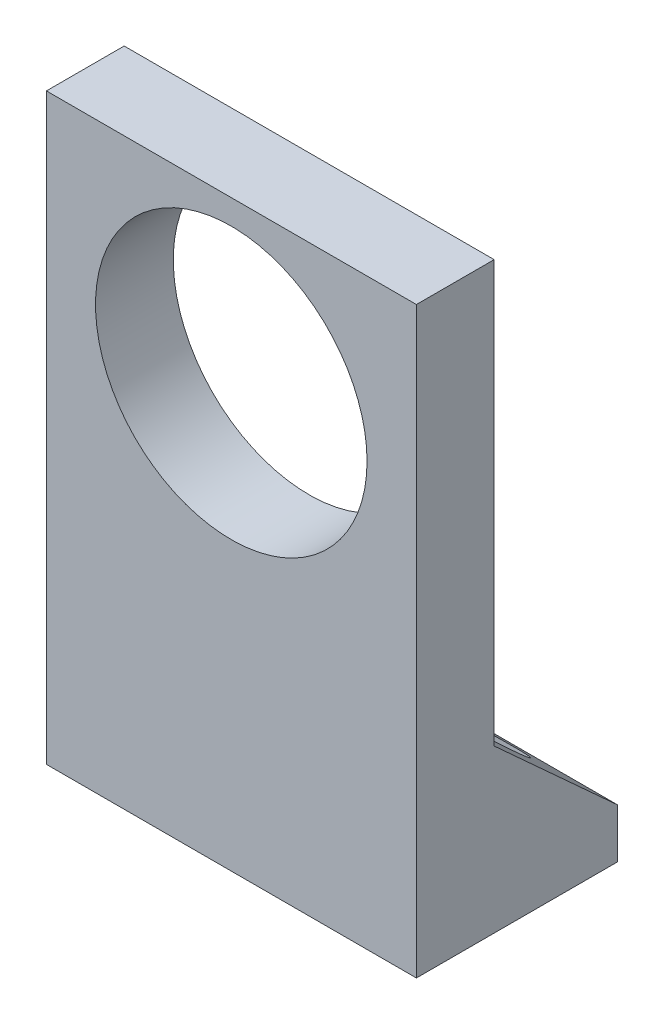
SolidWorks part; units mm, degrees
material "ABS"
ref_plane "Front Plane" through (0, 0, 0) normal (0, 0, 1) x (1, 0, 0)
ref_plane "Top Plane" through (0, 0, 0) normal (0, 1, 0) x (1, 0, 0)
ref_plane "Right Plane" through (0, 0, 0) normal (1, 0, 0) x (0, 0, -1)
sketch "Sketch1" plane through (0, 0, 0) normal (0, 0, 1) x (1, 0, 0)
  line L1 (-76.1871, 64.9281) -> (16.8129, 64.9281)
  line L2 (-76.1871, 64.9281) -> (-76.1871, -35.0719)
  line L3 (-76.1871, -35.0719) -> (16.8129, -35.0719)
  line L4 (16.8129, 64.9281) -> (16.8129, -35.0719)
  dimension "D1" = 93
  dimension "D2" = 100
extrude "Boss-Extrude2" add sketch "Sketch1" along normal blind 10 contours L1 L4 L3 L2
sketch "Sketch3" plane through (0, 0, 0) normal (0, 0, -1) x (-1, 0, 0)
  line L0 (76.1871, -35.0719) -> (-16.8129, -35.0719) construction
  line L1 (-16.8129, 64.9281) -> (-6.8129, 64.9281)
  line L2 (-16.8129, 64.9281) -> (-16.8129, -35.0719)
  line L3 (-16.8129, -35.0719) -> (-6.8129, -35.0719)
  line L4 (-6.8129, 64.9281) -> (-6.8129, -35.0719)
  line L5 (-16.8129, 64.9281) -> (-16.8129, -35.0719) construction
  dimension "D1" = 0
  dimension "D2" = 0
  dimension "D3" = 10
  dimension "D4" = 100
sketch "Sketch4" plane through (16.8129, 0, 0) normal (1, 0, 0) x (0, 0, -1)
  line L0 (-10, 64.9281) -> (-10, -35.0719) construction
  line L1 (-10, -5.0719) -> (0.01, -5.0719)
  line L2 (-10, -5.0719) -> (-10, -20.0719)
  line L3 (-10, -20.0719) -> (0.01, -20.0719)
  line L4 (0.01, -5.0719) -> (0.01, -20.0719)
  line L6 (-10, -35.0719) -> (0, -35.0719) construction
  dimension "D1" = 15
  dimension "D2" = 15
extrude "Boss-Extrude4" add sketch "Sketch4" along normal blind 24
sketch "Sketch5" plane through (0, -5.0719, 0) normal (0, 1, 0) x (1, 0, 0)
  line L0 (40.8129, -10) -> (16.8129, -10) construction
  line L2 (16.8129, 0) -> (16.8129, -10) construction
  circle A0 centre (26.8129, -5) radius 2
  dimension "D2" = 4
  dimension "D3" = 10
  dimension "D1" = 5
extrude "Cut-Extrude1" cut sketch "Sketch5" against normal blind 50
sketch "Sketch6" plane through (0, 0, 10) normal (0, 0, -1) x (-1, 0, 0)
  line L2 (76.1871, -35.0719) -> (-16.8129, -35.0719) construction
  line L3 (-16.8129, 64.9281) -> (-16.8129, -35.0719) construction
  circle A0 centre (-1.8129, -24.5719) radius 7.5
  dimension "D1" = 15
  dimension "D2" = 10.5
  dimension "D3" = 15
sketch "Sketch7" plane through (0, 0, 0) normal (0, 0, -1) x (-1, 0, 0)
  circle A0 centre (24.1871, 36.9281) radius 11
  circle A1 centre (24.1871, 36.9281) radius 9.3 construction
  dimension "D1" = 22
extrude "Cut-Extrude3" cut sketch "Sketch7" against normal blind 50
sketch "Sketch14" plane through (0, 0, 10) normal (0, 0, 1) x (1, 0, 0)
  line L0 (16.8129, 64.9281) -> (16.8129, -5.0719) construction
  line L1 (-44.6871, 15.7891) -> (16.8129, 15.7891)
  line L2 (-44.6871, 15.7891) -> (-44.6871, 57.7891)
  line L3 (-44.6871, 57.7891) -> (16.8129, 57.7891)
  line L4 (16.8129, 15.7891) -> (16.8129, 57.7891)
  dimension "D1" = 42
  dimension "D3" = 61.5
extrude "Cut-Extrude8" cut sketch "Sketch14" against normal blind 4
sketch "Sketch15" plane through (0, 0, 0) normal (0, 0, -1) x (-1, 0, 0)
  circle A0 centre (24.1871, 36.9281) radius 10
  circle A1 centre (24.1871, 36.9281) radius 11 construction
  dimension "D1" = 20
  dimension "D2" = 0
sketch "Sketch16" plane through (0, 0, 10) normal (0, 0, 1) x (1, 0, 0)
  line L0 (-43.6871, 56.9281) -> (14.3129, 56.9281) construction
  line L1 (-44.1871, 57.3281) -> (16.8129, 57.3281)
  line L2 (-44.1871, 57.3281) -> (-44.1871, 64.9281)
  line L3 (-44.1871, 64.9281) -> (16.8129, 64.9281)
  line L4 (16.8129, 57.3281) -> (16.8129, 64.9281)
  dimension "D1" = 0.4
sketch "Sketch17" plane through (0, 0, 10) normal (0, 0, 1) x (1, 0, 0)
  line L0 (16.8129, 15.7891) -> (16.8129, -5.0719) construction
  line L1 (-44.1871, 16.7281) -> (16.8129, 16.7281)
  line L2 (-44.1871, 16.7281) -> (-44.1871, -20.0719)
  line L3 (-44.1871, -20.0719) -> (16.8129, -20.0719)
  line L4 (16.8129, 16.7281) -> (16.8129, -20.0719)
  line L5 (-43.6871, 16.9281) -> (14.3129, 16.9281) construction
  line L6 (40.8129, -20.0719) -> (16.8129, -20.0719) construction
  line L9 (16.8129, -20.0719) -> (40.8129, -20.0719)
  line L10 (16.8129, -20.0719) -> (16.8129, -5.0719)
  line L11 (16.8129, -5.0719) -> (40.8129, -5.0719)
  line L12 (40.8129, -20.0719) -> (40.8129, -5.0719)
  line L13 (16.8129, -20.0719) -> (40.8129, -5.0719) construction
  line L14 (16.8129, -5.0719) -> (40.8129, -20.0719) construction
  point P16 (28.8129, -12.5719)
  dimension "D1" = 0.2
  dimension "D2" = 0
sketch "Sketch19" plane through (0, 0, 0) normal (0, 0, -1) x (-1, 0, 0)
  line L1 (-16.8129, 64.9281) -> (-16.8129, -35.0719) construction
  circle A0 centre (53.1871, 36.9281) radius 11
  circle A1 centre (24.1871, 36.9281) radius 10 construction
  dimension "D1" = 22
  dimension "D3" = 0
  dimension "D2" = 70
extrude "Cut-Extrude11" cut sketch "Sketch19" against normal blind 15
sketch "Sketch20" plane through (0, 0, 6) normal (0, 0, 1) x (1, 0, 0)
  circle A0 centre (-34.6871, 50.9281) radius 2
  circle A1 centre (5.3129, 50.9281) radius 2
  circle A2 centre (-34.6871, 22.9281) radius 2
  circle A3 centre (5.3129, 22.9281) radius 2
  arc A5 (-27.0471, 34.1316) -> (-27.0471, 39.7246) centre (-24.1871, 36.9281) ccw construction
  circle A6 centre (-24.1871, 36.9281) radius 11 construction
  dimension "D1" = 4
  dimension "D2" = 4
  dimension "D3" = 4
  dimension "D4" = 4
  dimension "D5" = 0
  dimension "D6" = 28
  dimension "D7" = 0
  dimension "D8" = 40
  dimension "D9" = 14
  dimension "D10" = 10.5
  dimension "D11" = 28
  dimension "D12" = 40
extrude "Cut-Extrude12" cut sketch "Sketch20" against normal blind 10
sketch "Sketch8" plane through (0, 64.9281, 0) normal (0, 1, 0) x (1, 0, 0)
  line L0 (-76.1871, -10) -> (16.8129, -10) construction
  line L5 (16.8129, 0) -> (12.3014, -10) construction
  line L6 (16.8129, -10) -> (7.8859, 0) construction
  line L8 (16.8129, -10) -> (16.8129, 0) construction
  line L9 (-76.1871, 0) -> (16.8129, 0) construction
  circle A0 centre (11.8129, -7) radius 1.4
  circle A1 centre (-13.1871, -7) radius 1.4
  point P4 (13.816, -6.6429)
  dimension "D1" = 25
  dimension "D2" = 5
  dimension "D3" = 2.8
  dimension "D4" = 7
  dimension "D5" = 7
sketch "Sketch21" plane through (0, 0, 0) normal (0, 0, -1) x (-1, 0, 0)
  line L1 (76.1871, 64.9281) -> (36.1871, 64.9281)
  line L2 (76.1871, 64.9281) -> (76.1871, 58.9281)
  line L3 (76.1871, 58.9281) -> (36.1871, 58.9281)
  line L4 (36.1871, 64.9281) -> (36.1871, 58.9281)
  dimension "D1" = 6
  dimension "D2" = 40
extrude "Boss-Extrude5" add sketch "Sketch21" along normal blind 27
sketch "Sketch22" plane through (0, 58.9281, 0) normal (0, -1, 0) x (1, 0, 0)
  line L0 (-76.1871, -27) -> (-76.1871, 0) construction
  line L1 (-36.1871, -27) -> (-76.1871, -27)
  line L2 (-36.1871, -27) -> (-36.1871, -20.7)
  line L3 (-36.1871, -20.7) -> (-76.1871, -20.7)
  line L4 (-76.1871, -27) -> (-76.1871, -20.7)
  dimension "D1" = 6.3
extrude "Boss-Extrude7" add sketch "Sketch22" along normal blind 40
sketch "Sketch23" plane through (0, 0, 10) normal (0, 0, 1) x (1, 0, 0)
  circle A0 centre (-53.1871, 36.9281) radius 8
  arc A1 (-44.6871, 43.9102) -> (-44.6871, 29.9459) centre (-53.1871, 36.9281) ccw construction
  dimension "D1" = 16
  dimension "D2" = 0
extrude "Cut-Extrude13" cut sketch "Sketch23" against normal blind 40
sketch "Sketch24" plane through (0, 0, 10) normal (0, 0, 1) x (1, 0, 0)
  line L1 (-76.1871, -35.0719) -> (42.0908, -35.0719)
  line L2 (-76.1871, -35.0719) -> (-76.1871, 6.7281)
  line L3 (-76.1871, 6.7281) -> (42.0908, 6.7281)
  line L4 (42.0908, -35.0719) -> (42.0908, 6.7281)
  dimension "D1" = 41.8
extrude "Cut-Extrude14" cut sketch "Sketch24" against normal blind 40
sketch "Sketch25" plane through (0, 0, 10) normal (0, 0, 1) x (1, 0, 0)
  line L5 (-44.6871, 29.9459) -> (-44.6871, 15.7891) construction
  line L6 (-76.1871, 6.7281) -> (-44.6871, 6.7281)
  line L7 (-76.1871, 6.7281) -> (-76.1871, 29.9281)
  line L8 (-76.1871, 29.9281) -> (-44.6871, 29.9281)
  line L9 (-44.6871, 6.7281) -> (-44.6871, 29.9281)
  arc A2 (-44.6871, 43.9102) -> (-44.6871, 29.9459) centre (-53.1871, 36.9281) ccw construction
  dimension "D1" = 7
extrude "Cut-Extrude15" cut sketch "Sketch25" against normal blind 20
sketch "Sketch26" plane through (0, 0, 6) normal (0, 0, 1) x (1, 0, 0)
  line L1 (-44.6871, 15.7891) -> (-36.2375, 15.7891)
  line L2 (-44.6871, 15.7891) -> (-44.6871, 21.6647)
  line L3 (-44.6871, 21.6647) -> (-36.2375, 21.6647)
  line L4 (-36.2375, 15.7891) -> (-36.2375, 21.6647)
  line L5 (-44.6871, 57.7891) -> (-36.2375, 57.7891)
  line L6 (-44.6871, 57.7891) -> (-44.6871, 52.1914)
  line L7 (-44.6871, 52.1914) -> (-36.2375, 52.1914)
  line L8 (-36.2375, 57.7891) -> (-36.2375, 52.1914)
  line L9 (6.8634, 52.1914) -> (14.3021, 52.1914)
  line L10 (6.8634, 52.1914) -> (6.8634, 57.7891)
  line L11 (6.8634, 57.7891) -> (14.3021, 57.7891)
  line L12 (14.3021, 52.1914) -> (14.3021, 57.7891)
  line L13 (6.8634, 20.9281) -> (14.3021, 20.9281)
  line L14 (6.8634, 20.9281) -> (6.8634, 15.7891)
  line L15 (6.8634, 15.7891) -> (14.3021, 15.7891)
  line L16 (14.3021, 20.9281) -> (14.3021, 15.7891)
  circle A0 centre (-34.6871, 22.9281) radius 2 construction
  circle A1 centre (-34.6871, 50.9281) radius 2 construction
  circle A2 centre (5.3129, 50.9281) radius 2 construction
  circle A3 centre (5.3129, 22.9281) radius 4
  circle A4 centre (5.3129, 50.9281) radius 4
  circle A5 centre (-34.6871, 50.9281) radius 4
  circle A6 centre (-34.6871, 22.9281) radius 4
  circle A7 centre (5.3129, 50.9281) radius 4
  circle A8 centre (5.3129, 22.9281) radius 4
  circle A9 centre (-34.6871, 50.9281) radius 4
  circle A10 centre (-34.6871, 22.9281) radius 4
  line M5 (-44.6871, 57.7891) -> (-44.6871, 43.9102)
  line M8 (-44.6871, 29.9281) -> (-44.6871, 15.7891)
  line M9 (-44.6871, 15.7891) -> (16.8129, 15.7891)
  line M11 (16.8129, 57.7891) -> (-44.6871, 57.7891)
  dimension "D1" = 8
  dimension "D2" = 8
  dimension "D3" = 8
  dimension "D4" = 8
extrude "Cut-Extrude18" cut sketch "Sketch26" against normal blind 3 contours A4 L9 L12 L10 M11 | A3 L14 L16 L13 M9 | A5 L8 L7 M11 M5 | A6 L3 L4 M8 M9
sketch "Sketch27" plane through (0, 0, 6) normal (0, 0, 1) x (1, 0, 0)
  circle A0 centre (5.3129, 50.9281) radius 4.1
  circle A1 centre (5.3129, 22.9281) radius 4
  circle A2 centre (-34.6871, 50.9281) radius 4.1
  circle A3 centre (-34.6871, 22.9281) radius 4.1
  dimension "D1" = 8.2
  dimension "D2" = 8.2
  dimension "D3" = 8
  dimension "D4" = 8.2
extrude "Cut-Extrude29" cut sketch "Sketch27" against normal blind 3
sketch "Sketch28" plane through (0, 0, 0) normal (0, 0, -1) x (-1, 0, 0)
  line L5 (-16.8129, 6.7281) -> (44.6871, 6.7281) construction
  line L6 (-16.8129, 64.9281) -> (12.6871, 64.9281)
  line L7 (-16.8129, 64.9281) -> (-16.8129, 6.7281)
  line L8 (-16.8129, 6.7281) -> (12.6871, 6.7281)
  line L9 (12.6871, 64.9281) -> (12.6871, 6.7281)
  circle A1 centre (34.6871, 22.9281) radius 2 construction
  dimension "D1" = 22
extrude "Cut-Extrude30" cut sketch "Sketch28" against normal blind 23
sketch "Sketch29" plane through (0, 15.7891, 0) normal (0, 1, 0) x (1, 0, 0)
  line L1 (-44.6871, -10) -> (-12.6871, -10)
  line L2 (-44.6871, -10) -> (-44.6871, -6)
  line L3 (-44.6871, -6) -> (-12.6871, -6)
  line L4 (-12.6871, -10) -> (-12.6871, -6)
extrude "Cut-Extrude31" cut sketch "Sketch29" against normal blind 23
sketch "Sketch31" plane through (0, 6.7281, 0) normal (0, -1, 0) x (1, 0, 0)
  line L1 (-44.6871, 6) -> (-12.6871, 6)
  line L2 (-44.6871, 6) -> (-44.6871, 0)
  line L3 (-44.6871, 0) -> (-12.6871, 0)
  line L4 (-12.6871, 6) -> (-12.6871, 0)
extrude "Boss-Extrude9" add sketch "Sketch31" along normal blind 6.6
sketch "Sketch32" plane through (0, 0, 6) normal (0, 0, 1) x (1, 0, 0)
  line L0 (-12.6871, 0.1281) -> (-12.6871, 57.7891) construction
  line L1 (-44.6871, 0.1281) -> (-12.6871, 0.1281)
  line L2 (-44.6871, 0.1281) -> (-44.6871, 6.1281)
  line L3 (-44.6871, 6.1281) -> (-12.6871, 6.1281)
  line L4 (-12.6871, 0.1281) -> (-12.6871, 6.1281)
  dimension "D1" = 6
extrude "Boss-Extrude10" add sketch "Sketch32" along normal blind 10
sketch "Sketch33" plane through (0, 6.1281, 0) normal (0, 1, 0) x (1, 0, 0)
  line L0 (-12.6871, -16) -> (-44.6871, -16) construction
  line L1 (-44.6871, -16) -> (-44.6871, -6) construction
  line L2 (-12.6871, -16) -> (-12.6871, -6) construction
  circle A0 centre (-37.6871, -11) radius 2
  circle A1 centre (-19.6871, -11) radius 2
  point P8 (-44.6871, -11)
  dimension "D1" = 4
  dimension "D2" = 4
  dimension "D3" = 0
  dimension "D4" = 5
  dimension "D5" = 7
  dimension "D6" = 7
extrude "Cut-Extrude32" cut sketch "Sketch33" against normal blind 10
sketch "Sketch34" plane through (-12.6871, 0, 0) normal (1, 0, 0) x (0, 0, -1)
  line L0 (-16, 6.1281) -> (-6, 6.1281)
  line L1 (-6, 6.1281) -> (-6, 14.0584)
  line L2 (-6, 6.1281) -> (-6, 57.7891) construction
  line L3 (-6, 14.0584) -> (-16, 6.1281)
extrude "Boss-Extrude11" add sketch "Sketch34" against normal up to vertex
sketch "Sketch35" plane through (0, 6.1281, 0) normal (0, -1, 0) x (1, 0, 0)
  circle A0 centre (-19.6871, 11) radius 3.5
  circle A1 centre (-37.6871, 11) radius 3.5
  dimension "D1" = 7
  dimension "D2" = 7
extrude "Cut-Extrude33" cut sketch "Sketch35" against normal blind 10
sketch "Sketch36" plane through (0, 18.9281, 0) normal (0, -1, 0) x (1, 0, 0)
  line L1 (-76.1871, -20.7) -> (-36.1871, -20.7)
  line L2 (-76.1871, -20.7) -> (-76.1871, -27)
  line L3 (-76.1871, -27) -> (-36.1871, -27)
  line L4 (-36.1871, -20.7) -> (-36.1871, -27)
extrude "Boss-Extrude12" add sketch "Sketch36" along normal up to vertex (18.8 mm away)
sketch "Sketch37" plane through (0, 0, -20.7) normal (0, 0, 1) x (1, 0, 0)
  line L0 (-76.1871, 0.1281) -> (-76.1871, 58.9281) construction
  line L1 (-36.1871, 0.1281) -> (-76.1871, 0.1281)
  line L2 (-36.1871, 0.1281) -> (-36.1871, 6.1281)
  line L3 (-36.1871, 6.1281) -> (-76.1871, 6.1281)
  line L4 (-76.1871, 0.1281) -> (-76.1871, 6.1281)
  dimension "D1" = 6
extrude "Boss-Extrude13" add sketch "Sketch37" along normal blind 16
sketch "Sketch38" plane through (0, 6.1281, 0) normal (0, 1, 0) x (1, 0, 0)
  line L0 (-36.1871, 4.7) -> (-76.1871, 4.7) construction
  line L2 (-36.1871, 4.7) -> (-36.1871, 20.7) construction
  circle A0 centre (-58.1871, 10.7) radius 2
  circle A1 centre (-45.1871, 10.7) radius 2
  dimension "D1" = 4
  dimension "D2" = 4
  dimension "D3" = 6
  dimension "D4" = 13
  dimension "D5" = 9
  dimension "D6" = 6
extrude "Cut-Extrude34" cut sketch "Sketch38" against normal blind 16
sketch "Sketch39" plane through (-36.1871, 0, 0) normal (1, 0, 0) x (0, 0, -1)
  line L0 (4.7, 6.1281) -> (20.7, 18.8781)
  line L1 (20.7, 6.1281) -> (20.7, 58.9281) construction
  line L2 (20.7, 18.8781) -> (20.7, 6.1281)
  line L3 (20.7, 6.1281) -> (4.7, 6.1281)
extrude "Boss-Extrude14" add sketch "Sketch39" against normal up to vertex (40 mm away)
sketch "Sketch40" plane through (0, 6.1281, 0) normal (0, -1, 0) x (1, 0, 0)
  circle A0 centre (-45.1871, -10.7) radius 3.5
  circle A1 centre (-58.1871, -10.7) radius 3.5
  dimension "D1" = 7
  dimension "D2" = 7
extrude "Cut-Extrude35" cut sketch "Sketch40" against normal blind 16
sketch "Sketch41" plane through (-12.6871, 0, 0) normal (1, 0, 0) x (0, 0, -1)
  line L1 (0, 64.9281) -> (-16, 64.9281)
  line L2 (0, 64.9281) -> (0, 0.1281)
  line L3 (0, 0.1281) -> (-16, 0.1281)
  line L4 (-16, 64.9281) -> (-16, 0.1281)
extrude "Cut-Extrude36" cut sketch "Sketch41" against normal blind 76
sketch "Sketch42" plane through (-36.1871, 0, 0) normal (1, 0, 0) x (0, 0, -1)
  line L0 (27, 64.9281) -> (0, 64.9281) construction
  line L1 (20.7, 58.9281) -> (0, 58.9281)
  line L2 (20.7, 58.9281) -> (20.7, 64.9281)
  line L3 (20.7, 64.9281) -> (0, 64.9281)
  line L4 (0, 58.9281) -> (0, 64.9281)
extrude "Cut-Extrude37" cut sketch "Sketch42" against normal blind 76
sketch "Sketch43" plane through (0, 0, -4.7) normal (0, 0, 1) x (1, 0, 0)
  line L1 (-76.1871, 0.1281) -> (-65.8661, 0.1281)
  line L2 (-76.1871, 0.1281) -> (-76.1871, 73.2032)
  line L3 (-76.1871, 73.2032) -> (-65.8661, 73.2032)
  line L4 (-65.8661, 0.1281) -> (-65.8661, 73.2032)
extrude "Cut-Extrude38" cut sketch "Sketch43" against normal blind 30
sketch "Sketch44" plane through (0, 0, -4.7) normal (0, 0, 1) x (1, 0, 0)
  line L1 (-36.1871, 0.1281) -> (-38.1871, 0.1281)
  line L2 (-36.1871, 0.1281) -> (-36.1871, 70.9113)
  line L3 (-36.1871, 70.9113) -> (-38.1871, 70.9113)
  line L4 (-38.1871, 0.1281) -> (-38.1871, 70.9113)
  dimension "D1" = 2
extrude "Cut-Extrude39" cut sketch "Sketch44" against normal blind 30
sketch "Sketch45" plane through (0, 0, -20.7) normal (0, 0, 1) x (1, 0, 0)
  line L0 (-65.8661, 64.9281) -> (-65.8661, 18.8781) construction
  line L1 (-38.1871, 64.9281) -> (-65.8661, 64.9281)
  line L2 (-38.1871, 64.9281) -> (-38.1871, 49.9281)
  line L3 (-38.1871, 49.9281) -> (-65.8661, 49.9281)
  line L4 (-65.8661, 64.9281) -> (-65.8661, 49.9281)
  circle A0 centre (-53.1871, 36.9281) radius 8 construction
  dimension "D1" = 13
extrude "Cut-Extrude40" cut sketch "Sketch45" against normal blind 30
sketch "Sketch46" plane through (0, 0, -4.7) normal (0, 0, 1) x (1, 0, 0)
  line L0 (-38.1871, 6.1281) -> (-38.1871, 0.1281) construction
  line L1 (-65.8661, 0.1281) -> (-38.1871, 0.1281)
  line L2 (-65.8661, 0.1281) -> (-65.8661, 2.6681)
  line L3 (-65.8661, 2.6681) -> (-38.1871, 2.6681)
  line L4 (-38.1871, 0.1281) -> (-38.1871, 2.6681)
  dimension "D1" = 2.54
extrude "Cut-Extrude41" cut sketch "Sketch46" against normal blind 110
sketch "Sketch47" plane through (0, 0, -20.7) normal (0, 0, 1) x (1, 0, 0)
  circle A0 centre (-53.1871, 36.9281) radius 11
  circle A1 centre (-53.1871, 36.9281) radius 8 construction
  dimension "D1" = 0
  dimension "D2" = 22
extrude "Cut-Extrude42" cut sketch "Sketch47" against normal blind 20
sketch "Sketch48" plane through (-65.8661, 0, 0) normal (-1, 0, 0) x (0, 0, 1)
  line L0 (-27, 49.9281) -> (-20.7, 49.9281)
  line L1 (-20.7, 49.9281) -> (-20.7, 18.8781)
  line L2 (-20.7, 18.8781) -> (-4.7, 6.1281)
  line L3 (-4.7, 6.1281) -> (-4.7, 2.6681)
  line L4 (-4.7, 2.6681) -> (-27, 2.6681)
  line L5 (-27, 2.6681) -> (-27, 49.9281)
  line L6 (-20.7, 25.9281) -> (-20.7, 47.9281) construction
extrude "Boss-Extrude16" add sketch "Sketch48" along normal blind 2.3
sketch "Sketch49" plane through (-68.1661, 0, 0) normal (-1, 0, 0) x (0, 0, 1)
  line L0 (-4.7, 2.6681) -> (-4.7, 6.1281)
  line L1 (-4.7, 6.1281) -> (-20.7, 18.8781)
  line L2 (-20.7, 18.8781) -> (-20.7, 2.6681)
  line L3 (-27, 2.6681) -> (-4.7, 2.6681) construction
  line L4 (-20.7, 2.6681) -> (-4.7, 2.6681)
extrude "Cut-Extrude43" cut sketch "Sketch49" against normal blind 50
sketch "Sketch51" plane through (0, 0, -27) normal (0, 0, -1) x (-1, 0, 0)
  line L0 (68.1661, 49.9281) -> (68.1661, 2.6681) construction
  line L1 (38.1871, 2.6681) -> (68.1661, 2.6681)
  line L2 (38.1871, 2.6681) -> (38.1871, 6.6681)
  line L3 (38.1871, 6.6681) -> (68.1661, 6.6681)
  line L4 (68.1661, 2.6681) -> (68.1661, 6.6681)
  dimension "D1" = 4
extrude "Boss-Extrude17" add sketch "Sketch51" along normal blind 10
sketch "Sketch52" plane through (0, 6.6681, 0) normal (0, 1, 0) x (1, 0, 0)
  line L0 (-68.1661, 37) -> (-38.1871, 37) construction
  line L1 (-38.1871, 37) -> (-38.1871, 27) construction
  line L2 (-68.1661, 37) -> (-68.1661, 27) construction
  circle A0 centre (-45.1871, 32) radius 2
  circle A1 centre (-61.1661, 32) radius 2
  dimension "D1" = 4
  dimension "D2" = 4
  dimension "D3" = 0
  dimension "D4" = 5
  dimension "D5" = 7
  dimension "D6" = 7
extrude "Cut-Extrude44" cut sketch "Sketch52" against normal blind 10
sketch "Sketch53" plane through (-68.1661, 0, 0) normal (-1, 0, 0) x (0, 0, 1)
  line L0 (-37, 6.6681) -> (-27, 6.6681)
  line L1 (-27, 6.6681) -> (-27, 15.7954)
  line L2 (-27, 49.9281) -> (-27, 6.6681) construction
  line L3 (-27, 15.7954) -> (-37, 6.6681)
extrude "Boss-Extrude18" add sketch "Sketch53" against normal up to vertex (29.979 mm away)
sketch "Sketch54" plane through (0, 6.6681, 0) normal (0, -1, 0) x (1, 0, 0)
  circle A0 centre (-61.1661, -32) radius 3.5
  circle A1 centre (-45.1871, -32) radius 3.5
  dimension "D1" = 7
  dimension "D2" = 7
extrude "Cut-Extrude45" cut sketch "Sketch54" against normal blind 10
